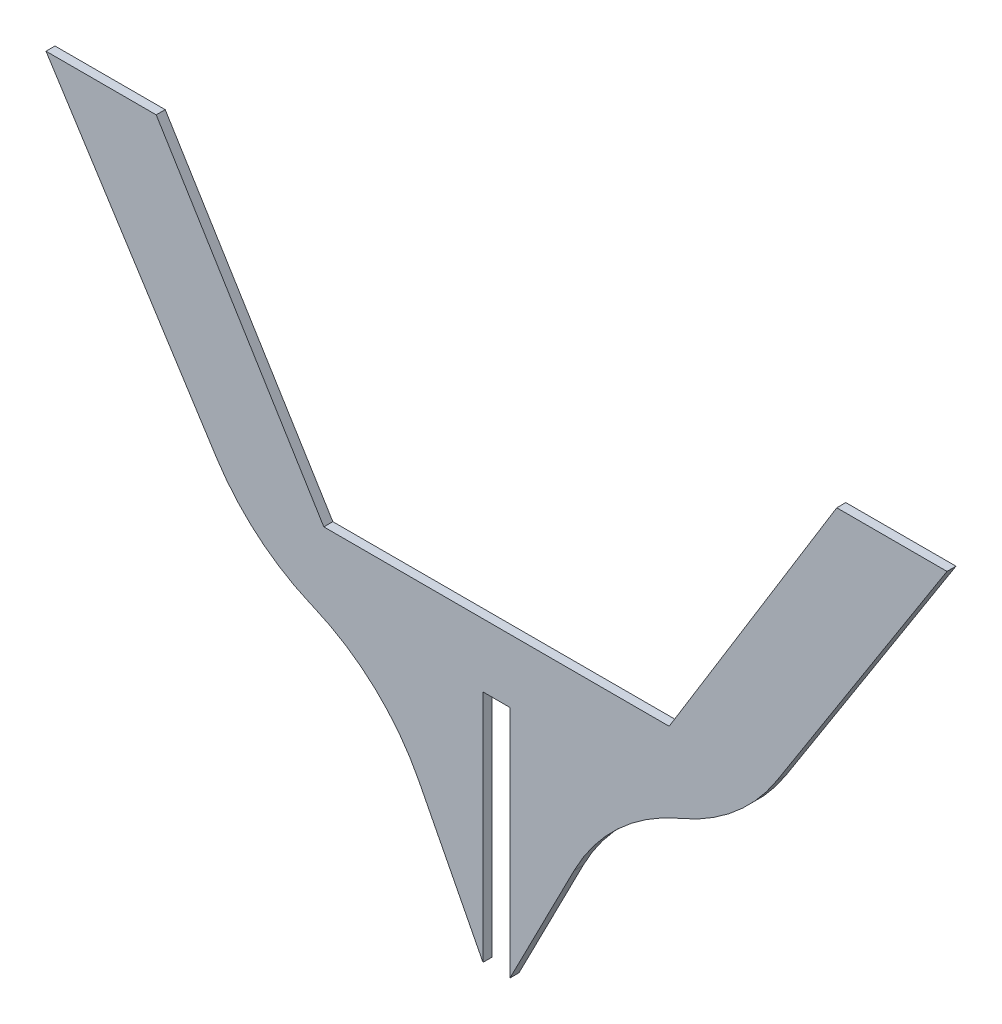
SolidWorks part; units mm, degrees
ref_plane "Plan de face" through (0, 0, 0) normal (0, 0, 1) x (1, 0, 0)
ref_plane "Plan de dessus" through (0, 0, 0) normal (0, 1, 0) x (1, 0, 0)
ref_plane "Plan de droite" through (0, 0, 0) normal (1, 0, 0) x (0, 0, -1)
sketch "Esquisse1" plane through (0, 0, 0) normal (0, 1, 0) x (1, 0, 0)
  point P0 (0, 27.1237)
sketch "Esquisse3" plane through (0, 0, 0) normal (0, 0, 1) x (1, 0, 0)
  line L49 (13.3579, 115.9133) -> (57.6644, 96.9823)
  line L50 (57.6644, 96.9823) -> (90.5528, 32.7885)
  line L51 (90.5528, 32.7885) -> (90.5528, 110.7885)
  line L52 (99.5528, 110.7885) -> (90.5528, 110.7885)
  line L54 (95.0528, 110.7885) -> (95.0528, 131.8781) construction
  line L55 (99.5528, 32.7885) -> (99.5528, 110.7885)
  line L56 (176.7478, 115.9133) -> (132.4413, 96.9823)
  line L57 (245.0528, 222.7885) -> (176.7478, 115.9133)
  line L61 (208.3571, 222.7885) -> (152.5451, 131.8781)
  line L63 (132.4413, 96.9823) -> (99.5528, 32.7885)
  line L65 (152.5451, 131.8781) -> (37.5606, 131.8781)
  line L66 (208.3571, 222.7885) -> (245.0528, 222.7885)
  line L67 (-18.2514, 222.7885) -> (-54.9472, 222.7885)
  line L68 (-18.2514, 222.7885) -> (37.5606, 131.8781)
  line L69 (-54.9472, 222.7885) -> (13.3579, 115.9133)
  point P2 (29.255, -24.3766)
  point P3 (132.0096, 39.6085)
  point P6 (191.6864, 11.8045)
  point P17 (0, 0)
  point P18 (191.6864, 223.1517)
  point P19 (0, 0)
  point P22 (0, 0)
  point P23 (41.4305, -14.6483)
  point P24 (-19.5502, 19.356)
  point P25 (0, 0)
  point P26 (132.0096, -19.4256)
  point P27 (187.4131, 21.8029)
  point P28 (178.4417, 121.3816)
  point P29 (141.5312, 141.2848)
  point P30 (132.4413, 96.9823)
  point P31 (176.7478, 115.9133)
  point P32 (208.3571, 222.7885)
  point P33 (152.5451, 131.8781)
  dimension "D2" = 112
  dimension "D3" = 300
  dimension "D6" = 9
  dimension "D11" = 78
extrude "Boss.-Extru.3" add sketch "Esquisse3" along normal blind 3
fillet "Congé2" radius 70 4 edges at (57.6644, 96.9823, 1.5) (13.3579, 115.9133, 1.5) (176.7478, 115.9133, 1.5) (132.4413, 96.9823, 1.5)
